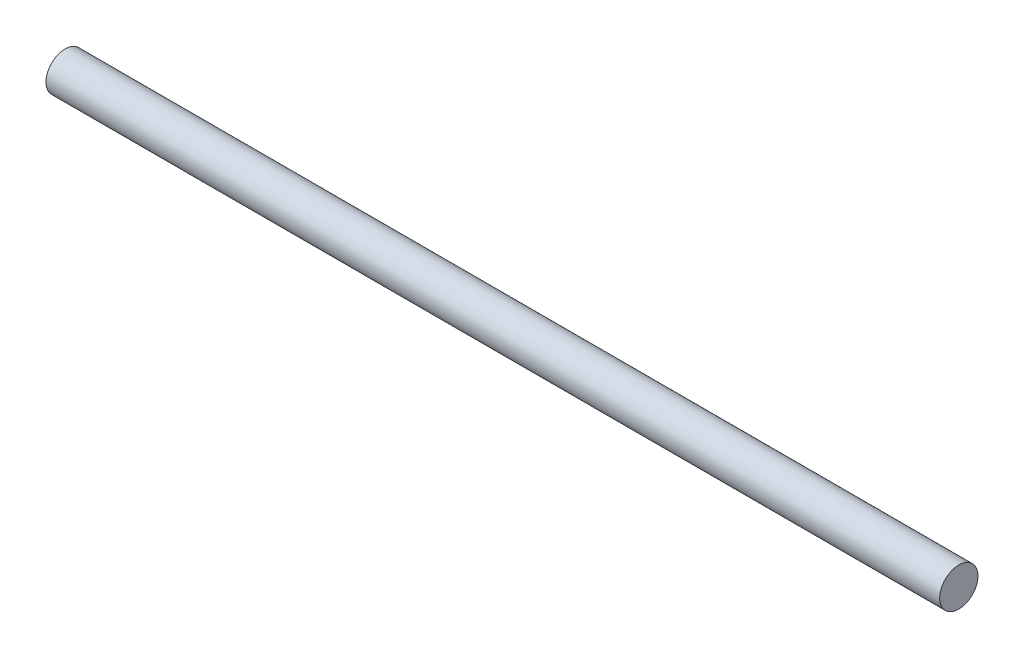
SolidWorks part; units mm, degrees
ref_plane "Front Plane" through (0, 0, 0) normal (0, 0, 1) x (1, 0, 0)
ref_plane "Top Plane" through (0, 0, 0) normal (0, 1, 0) x (1, 0, 0)
ref_plane "Right Plane" through (0, 0, 0) normal (1, 0, 0) x (0, 0, -1)
sketch "Sketch1" plane through (0, 0, 0) normal (1, 0, 0) x (0, 0, -1)
  circle A0 centre (0, 0) radius 1.5
  dimension "D1" = 3
extrude "Boss-Extrude1" add sketch "Sketch1" along normal mid plane 70
